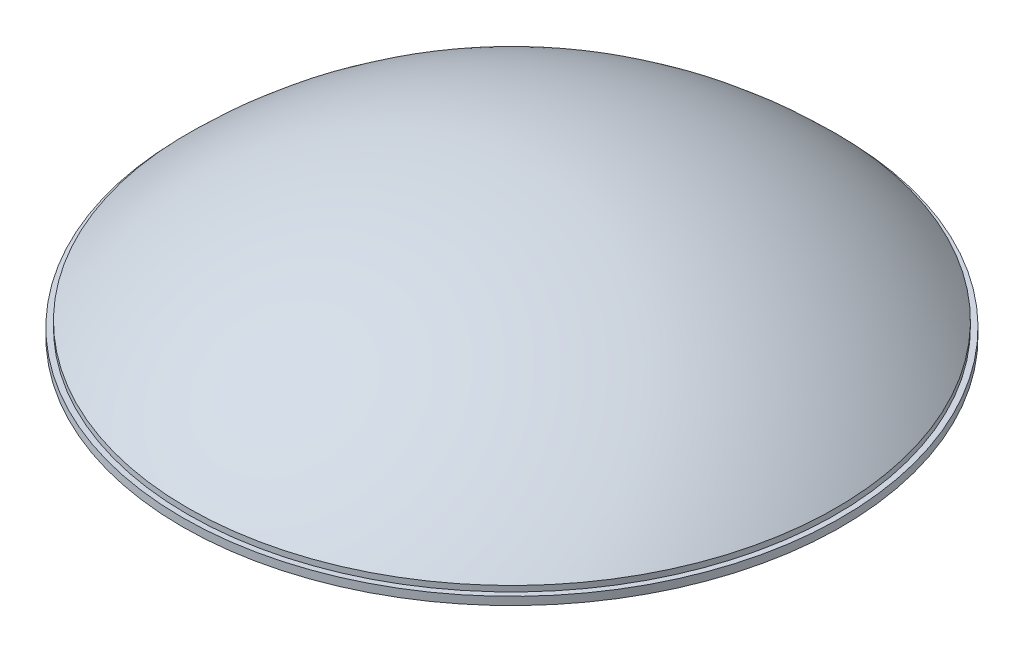
SolidWorks part; units mm, degrees
material "Acrylic (Medium-high impact)"
ref_plane "Front" through (0, 0, 0) normal (0, 0, 1) x (1, 0, 0)
ref_plane "Top" through (0, 0, 0) normal (0, 1, 0) x (1, 0, 0)
ref_plane "Right" through (0, 0, 0) normal (1, 0, 0) x (0, 0, -1)
sketch "Sketch1" plane through (0, 0, 0) normal (1, 0, 0) x (0, 0, -1)
  line L0 (0, 342) -> (0, 332) construction
  line L1 (242.6582, 241) -> (246.5, 241) construction
  line L2 (246.5, 241) -> (246.5, 229) construction
  line L3 (246.5, 229) -> (240.3809, 229) construction
  line L4 (0, 332) -> (0, 0) construction
  line L5 (0, 0) -> (53.5006, 337.7894) construction
  line L6 (26.55, 278) -> (44.0309, 278) construction
  line L7 (26.55, 258) -> (40.8632, 258) construction
  line L8 (26.25, 284) -> (26.25, 235.5) construction
  line L9 (23.25, 232.5) -> (0, 232.5) construction
  line L10 (26.55, 278) -> (26.55, 258) construction
  line L11 (22.2, 232.5) -> (22.2, 210.5) construction
  line L12 (21.2, 209.5) -> (0, 209.5) construction
  line L13 (49.2591, 319) -> (50.7013, 328.1057) construction
  line L14 (49.2591, 319) -> (39.2252, 310.1228) construction
  line L15 (29.1813, 290.9057) -> (36.1857, 297.6697) construction
  line L16 (27, 278) -> (27, 279) construction
  line L17 (27, 279) -> (42, 279) construction
  line L18 (42, 279) -> (42, 278) construction
  line L19 (26.4, 284) -> (43.7156, 284) construction
  line L20 (43.7156, 284) -> (48.9147, 316.8261) construction
  line L21 (48.4509, 317.3504) -> (40.8872, 310.6585) construction
  line L22 (40.5498, 309.9096) -> (40.5498, 304.1375) construction
  line L23 (29.2855, 290.7978) -> (36.2899, 297.5618) construction
  line L24 (36.2899, 297.5618) -> (38.7788, 299.9654) construction
  line L25 (48.4509, 317.3504) -> (48.9147, 316.8261) construction
  line L26 (30, 284) -> (30, 279) construction
  line L27 (40.7818, 311.5) -> (41.2457, 310.9757) construction
  line L28 (40, 284) -> (40, 279) construction
  line L29 (49.2591, 319) -> (49.7229, 318.4757) construction
  line L30 (49.7229, 318.4757) -> (48.4509, 317.3504) construction
  arc A0 (0, 342) -> (242.6582, 241) centre (0, 0) cw construction
  arc A1 (0, 332) -> (240.3809, 229) centre (0, 0) cw construction
  arc A2 (0, 330) -> (36.419, 314.7024) centre (0, 279) cw construction
  arc A3 (26.25, 284) -> (29.1813, 290.9057) centre (35.85, 284) cw construction
  arc A4 (23.25, 232.5) -> (26.25, 235.5) centre (23.25, 235.5) ccw construction
  arc A5 (36.1857, 297.6697) -> (36.419, 314.7024) centre (27.8498, 306.3018) ccw construction
  arc A6 (21.2, 209.5) -> (22.2, 210.5) centre (21.2, 210.5) ccw construction
  arc A7 (26.4, 284) -> (29.2855, 290.7978) centre (35.85, 284) cw construction
  arc A8 (40.5498, 309.9096) -> (40.8872, 310.6585) centre (41.5498, 309.9096) cw construction
  arc A9 (36.2899, 297.5618) -> (36.5261, 314.8074) centre (27.8498, 306.3018) ccw construction
  arc A10 (38.7788, 299.9654) -> (40.5498, 304.1375) centre (34.7498, 304.1375) ccw construction
  point P21 (0, 279)
  point P34 (22.2, 209.5)
  dimension "D1" = 342
  dimension "D2" = 332
  dimension "D16" = 51
  dimension "D17" = 9.6
  dimension "D19" = 140.5
  dimension "D20" = 12
  dimension "D21" = 51.5
  dimension "D23" = 3
  dimension "D24" = 1
  dimension "D31" = 1
  dimension "D32" = 5.8
  dimension "D3" = 241
  dimension "D4" = 229
  dimension "D5" = 246.5
  dimension "D6" = 9
  dimension "D7" = 278
  dimension "D8" = 20
  dimension "D9" = 26.25
  dimension "D10" = 0.3
  dimension "D11" = 232.5
  dimension "D12" = 23
  dimension "D13" = 22.2
  dimension "D14" = 1.25
  dimension "D15" = 97.5
  dimension "D18" = 44
  dimension "D22" = 13
  dimension "D25" = 15
  dimension "D26" = 1
  dimension "D27" = 27
  dimension "D28" = 0.7
  dimension "D29" = 0.7
  dimension "D33" = 30
  dimension "D34" = 5
  dimension "D35" = 10
  dimension "D36" = 0.7
  dimension "D37" = 7.5
  dimension "D30" = 0.15
sketch "Sketch2" plane through (0, 0, 0) normal (1, 0, 0) x (0, 0, -1)
  line L0 (246.5, 236.9583) -> (242.5, 236.9583)
  line L1 (242.5, 236.9583) -> (242.5, 241.1592)
  line L2 (246.5, 236.9583) -> (246.5, 230.9583)
  line L3 (0, 342) -> (0, 332) construction
  line L4 (244.5, 228.547) -> (-244.5, 228.547) construction
  line L5 (246.5, 237.0691) -> (246.5, 236.9583) construction
  line L6 (246.5, 241) -> (246.5, 229) construction
  line L7 (0, 342) -> (0, 332)
  line L8 (244.5, 228.547) -> (244.5, 230.96) construction
  line L9 (244.5, 229.7535) -> (240.1118, 229.7535) construction
  line L12 (246.5, 230.9583) -> (238.5, 230.9583)
  arc A1 (240.3809, 229) -> (0, 332) centre (0, 0) ccw construction
  arc A2 (246.5, 237.0691) -> (242.5, 241.1592) centre (0, 0) ccw construction
  arc A3 (242.5, 241.1592) -> (0, 342) centre (0, 0) ccw
  arc A4 (238.5, 230.9583) -> (0, 332) centre (0, 0) ccw
  dimension "D1" = 4
  dimension "D2" = 8
  dimension "D3" = 6
  dimension "D4" = 2.4113
  dimension "D5" = 4.3882
revolve "Revolve1" add sketch "Sketch2" angle 360 about L7
